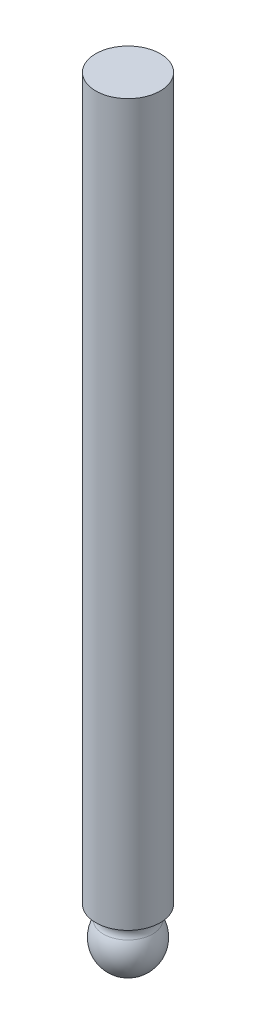
SolidWorks part; units mm, degrees
ref_plane "Front Plane" through (0, 0, 0) normal (0, 0, 1) x (1, 0, 0)
ref_plane "Top Plane" through (0, 0, 0) normal (0, 1, 0) x (1, 0, 0)
ref_plane "Right Plane" through (0, 0, 0) normal (1, 0, 0) x (0, 0, -1)
sketch "Sketch1" plane through (0, 0, 0) normal (0, 1, 0) x (1, 0, 0)
  circle A0 centre (0, 0) radius 3.556
  dimension "D1" = 7.112
extrude "Boss-Extrude1" add sketch "Sketch1" along normal blind 79.375
sketch "Sketch2" plane through (0, 0, 0) normal (0, 0, 1) x (1, 0, 0)
  line L0 (-3.556, 0) -> (3.556, 0) construction
  line L1 (-3.556, 0) -> (3.556, 0) construction
  line L2 (0, 0) -> (0, -6.35) construction
  line L3 (3.556, 0) -> (0, 0)
  line L4 (0, 0) -> (0, -6.35)
  arc A0 (0, -6.35) -> (2.7071, -1.516) centre (0, -3.175) ccw
  arc A1 (2.7071, -1.516) -> (3.556, 0) centre (3.556, -0.9957) cw
  dimension "D1" = 6.35
revolve "Revolve1" add sketch "Sketch2" angle 360 about L4
